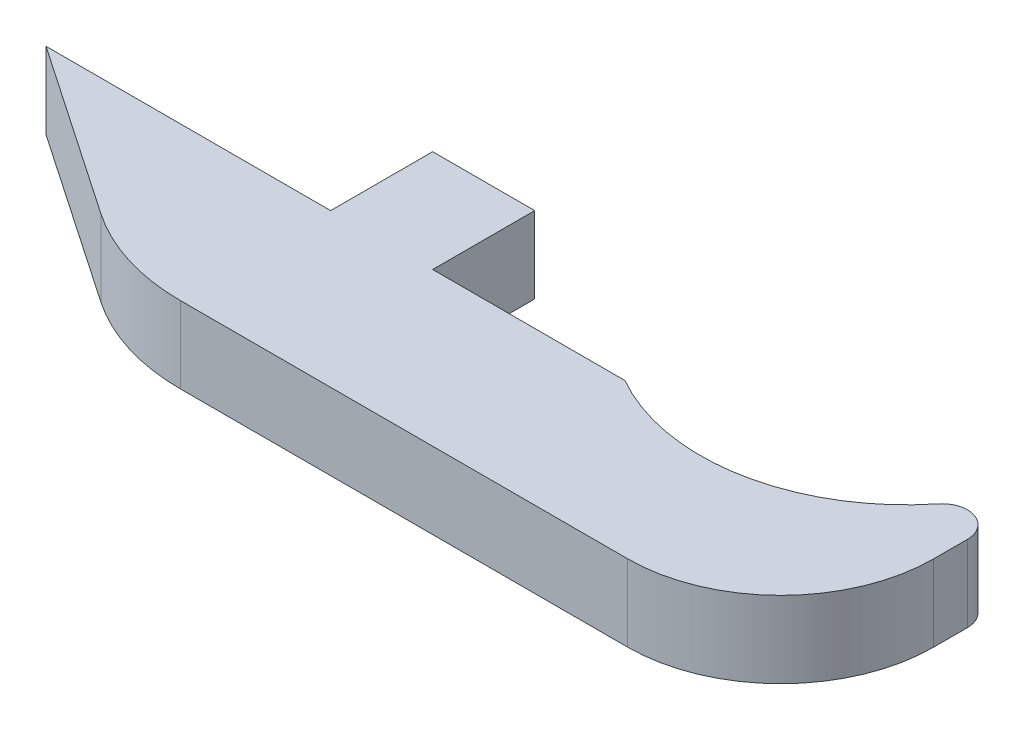
SolidWorks part; units mm, degrees
material "AISI 4130 Steel, annealed at 865C"
ref_plane "X-Y Datum" through (0, 0, 0) normal (0, 0, 1) x (1, 0, 0)
ref_plane "X-Z Datum" through (0, 0, 0) normal (0, 1, 0) x (1, 0, 0)
ref_plane "Y-Z Datum" through (0, 0, 0) normal (1, 0, 0) x (0, 0, -1)
sketch "Sketch1" plane through (0, 0, 0) normal (0, 1, 0) x (1, 0, 0)
  line L0 (20.8895, 0) -> (0, 0) construction
  line L1 (45.593, 0) -> (0, 0)
  line L2 (45.593, 0) -> (45.593, 11.1252)
  line L3 (17.145, -9.525) -> (58.42, -9.525)
  line L4 (58.42, 11.1252) -> (58.42, -9.525)
  line L5 (3.175, 0) -> (17.145, -9.525)
  circle A0 centre (45.593, 11.1252) radius 12.827
  dimension "D3" = 25.654
  dimension "D5" = 9.525
  dimension "D1" = 45.593
  dimension "D2" = 11.1252
  dimension "D4" = 3.175
  dimension "D6" = 41.275
extrude "Boss-Extrude1" add sketch "Sketch1" along normal blind 4.7625
fillet "Fillet1" radius 9.525 1 edges at (58.42, 2.3813, 9.525)
fillet "Fillet2" radius 1.5875 1 edges at (58.42, 2.3813, -11.1252)
fillet "Fillet4" radius 12.7 1 edges at (17.145, 2.3813, 9.525)
sketch "Sketch2" plane through (0, 0, 0) normal (0, -1, 0) x (1, 0, 0)
  line L1 (27.2395, -6.35) -> (27.2395, 0)
  line L2 (-7.0505, -6.35) -> (27.8745, -6.35) construction
  line L3 (27.2395, 0) -> (20.8895, 0)
  line L4 (27.2395, 0) -> (27.2395, -6.35)
  line L5 (27.2395, -6.35) -> (20.8895, -6.35)
  line L6 (20.8895, 0) -> (20.8895, -6.35)
  line L7 (33.5895, 0) -> (33.5895, -6.35) construction
  line M6 (3.175, 0) -> (39.2085, 0)
  dimension "D1" = 6.35
  dimension "D2" = 6.35
extrude "Boss-Extrude2" add sketch "Sketch2" against normal blind 4.7625 contours L6 L5 L1 M6
